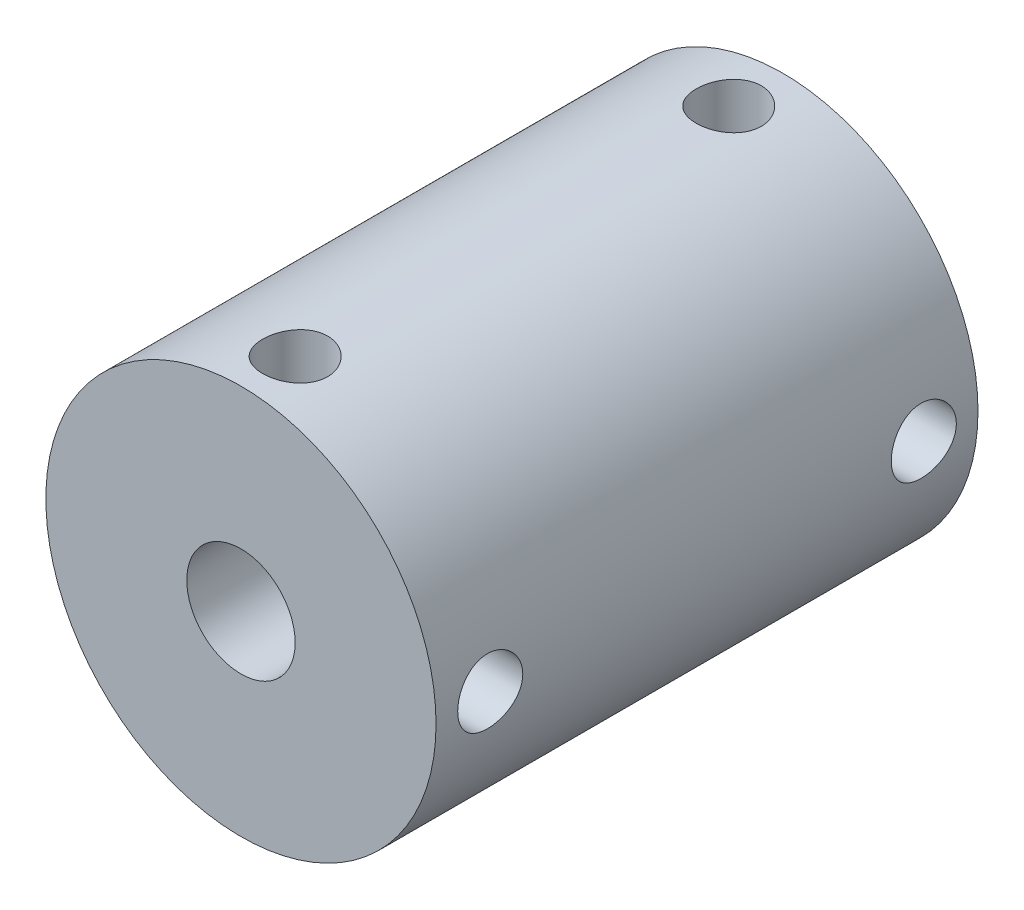
SolidWorks part; units mm, degrees
ref_plane "Front Plane" through (0, 0, 0) normal (0, 0, 1) x (1, 0, 0)
ref_plane "Top Plane" through (0, 0, 0) normal (0, 1, 0) x (1, 0, 0)
ref_plane "Right Plane" through (0, 0, 0) normal (1, 0, 0) x (0, 0, -1)
sketch "Sketch1" plane through (0, 0, 0) normal (0, 0, 1) x (1, 0, 0)
  circle A0 centre (0, 0) radius 9
  dimension "D1" = 18
extrude "Boss-Extrude1" add sketch "Sketch1" along normal mid plane 25
sketch "Sketch2" plane through (0, 0, 12.5) normal (0, 0, 1) x (1, 0, 0)
  circle A0 centre (0, 0) radius 2.5
  dimension "D1" = 5
extrude "Cut-Extrude1" cut sketch "Sketch2" against normal through all
sketch "Sketch3" plane through (0, 0, 0) normal (0, 1, 0) x (1, 0, 0)
  circle A0 centre (0, 10) radius 1.5
  circle A1 centre (0, -10) radius 1.5
  dimension "D1" = 3
  dimension "D2" = 3
  dimension "D3" = 10
  dimension "D4" = 10
extrude "Cut-Extrude2" cut sketch "Sketch3" along normal through all
sketch "Sketch4" plane through (0, 0, 0) normal (1, 0, 0) x (0, 0, -1)
  circle A0 centre (-10, 0) radius 1.5
  circle A1 centre (10, 0) radius 1.5
  dimension "D1" = 3
  dimension "D2" = 3
  dimension "D3" = 10
  dimension "D4" = 10
extrude "Cut-Extrude3" cut sketch "Sketch4" along normal through all
